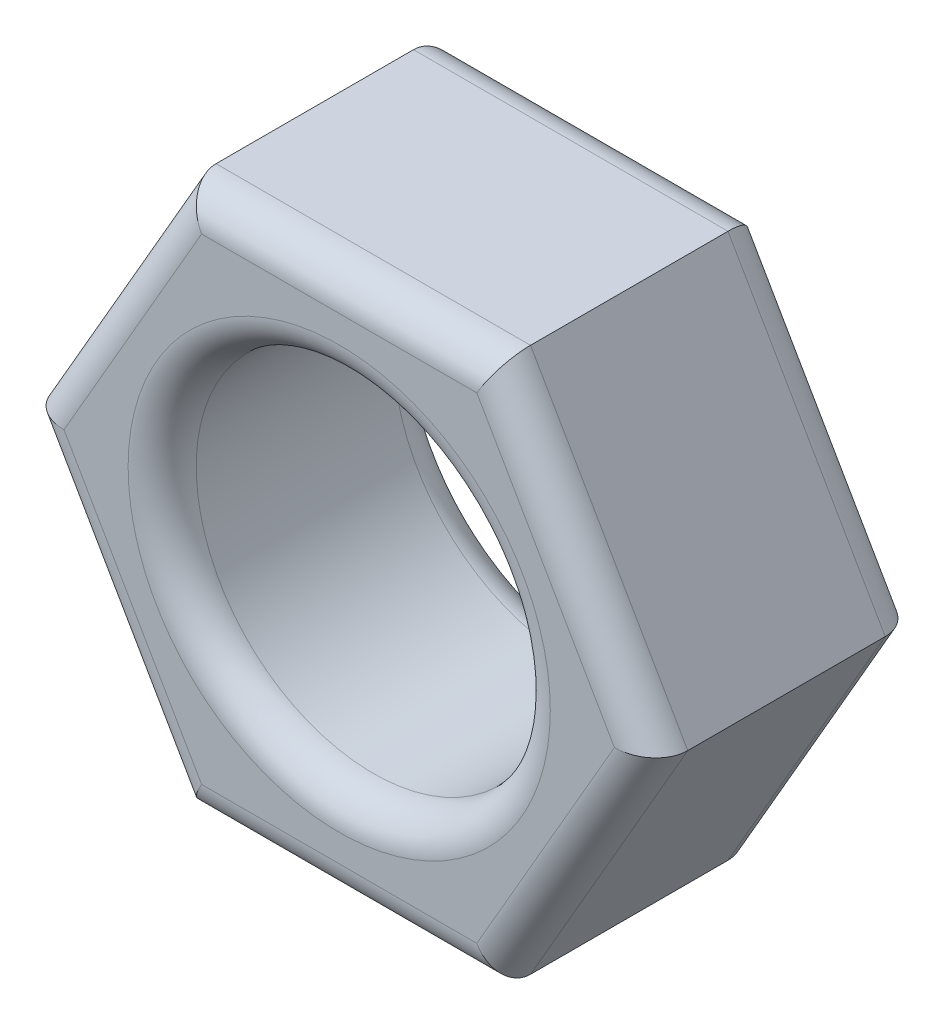
SolidWorks part; units mm, degrees
ref_plane "前视基准面" through (0, 0, 0) normal (0, 0, 1) x (1, 0, 0)
ref_plane "上视基准面" through (0, 0, 0) normal (0, 1, 0) x (1, 0, 0)
ref_plane "右视基准面" through (0, 0, 0) normal (1, 0, 0) x (0, 0, -1)
other "Configuration Table"
sketch "草图1" plane through (0, 0, 0) normal (0, 0, 1) x (1, 0, 0)
  line L1 (4.6188, 0) -> (2.3094, 4)
  line L2 (2.3094, 4) -> (-2.3094, 4)
  line L3 (-2.3094, 4) -> (-4.6188, 0)
  line L4 (-4.6188, 0) -> (-2.3094, -4)
  line L5 (-2.3094, -4) -> (2.3094, -4)
  line L6 (2.3094, -4) -> (4.6188, 0)
  circle A0 centre (0, 0) radius 4 construction
  circle A1 centre (0, 0) radius 2.6
  dimension "D2" = 5.2
  dimension "D1" = 8
extrude "凸台-拉伸1" add sketch "草图1" along normal blind 3.9
fillet "圆角1" radius 0.5 14 edges at (2.6, 0, 0) (3.4641, 2, 0) (0, 4, 0) (-3.4641, 2, 0) (-3.4641, -2, 0) (0, -4, 0) (3.4641, -2, 0) (2.6, 0, 3.9) (0, -4, 3.9) (-3.4641, -2, 3.9) (-3.4641, 2, 3.9) (0, 4, 3.9) (3.4641, 2, 3.9) (3.4641, -2, 3.9)
